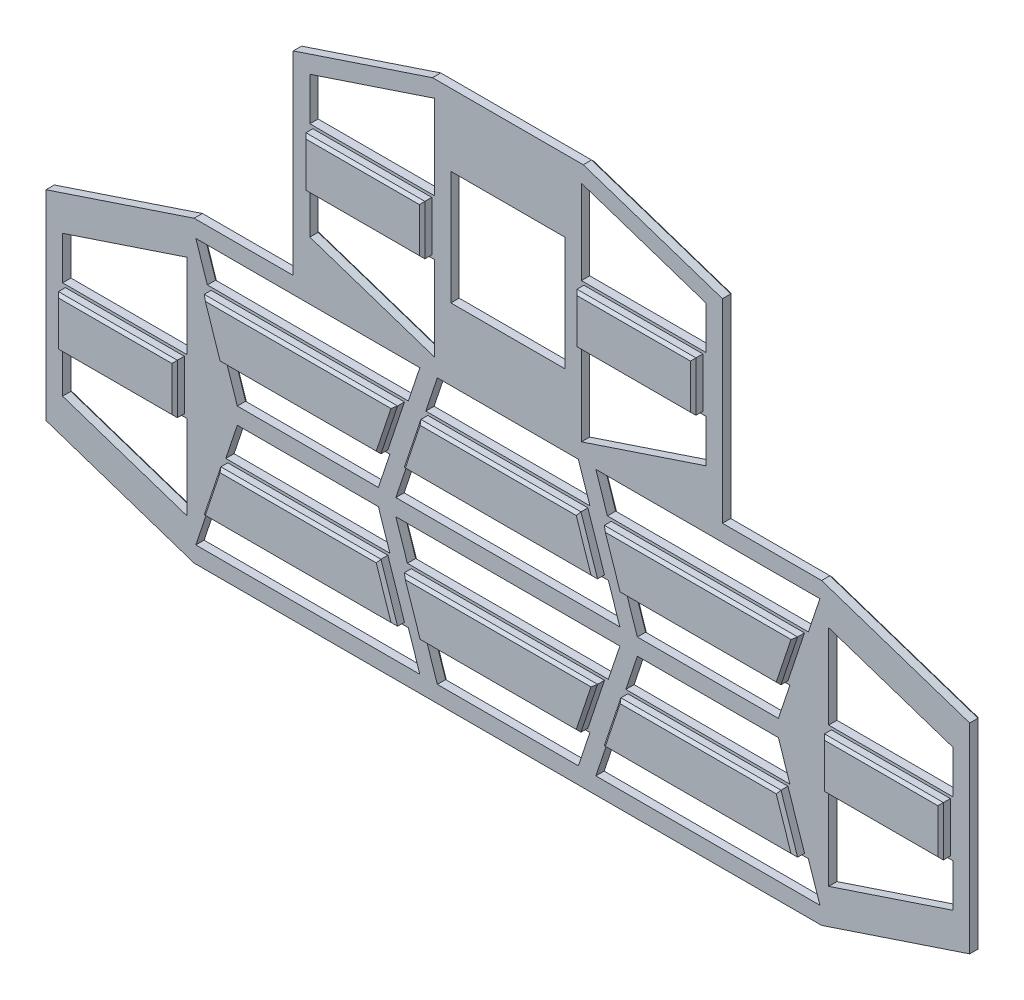
SolidWorks part; units mm, degrees
ref_plane "Front Plane" through (0, 0, 0) normal (0, 0, 1) x (1, 0, 0)
ref_plane "Top Plane" through (0, 0, 0) normal (0, 1, 0) x (1, 0, 0)
ref_plane "Right Plane" through (0, 0, 0) normal (1, 0, 0) x (0, 0, -1)
sketch "Sketch1" plane through (0, 0, 0) normal (0, 0, 1) x (1, 0, 0)
  line L0 (0, 37.8111) -> (0, -97.9817) construction
  line L1 (-53.0722, 0) -> (46.9222, 0) construction
  line L2 (-13.3, 20.25) -> (-13.3, -20.25)
  line L3 (-10.3, -10.3) -> (10.3, -10.3)
  line L4 (-10.3, -10.3) -> (-10.3, 10.3)
  line L5 (-10.3, 10.3) -> (10.3, 10.3)
  line L6 (10.3, -10.3) -> (10.3, 10.3)
  line L7 (-10.3, -10.3) -> (10.3, 10.3) construction
  line L8 (-10.3, 10.3) -> (10.3, -10.3) construction
  line L9 (-13.3, 20.25) -> (-35.8, 12.75)
  line L10 (-35.8, 12.75) -> (-35.8, -12.75)
  line L11 (-13.3, -20.25) -> (-35.8, -12.75)
  line L12 (13.3, -20.25) -> (35.8, -12.75)
  line L13 (35.8, 12.75) -> (35.8, -12.75)
  line L14 (13.3, 20.25) -> (35.8, 12.75)
  line L15 (13.3, 20.25) -> (13.3, -20.25)
  line L32 (48.9123, -48.75) -> (56.4123, -71.25)
  line L68 (-13.6368, 23.3) -> (13.6368, 23.3)
  line L69 (-38.8, 14.9123) -> (-13.6368, 23.3)
  line L70 (-90.3613, -47.25) -> (102.7928, -47.25) construction
  line L87 (-12.75, -23.25) -> (12.75, -23.25)
  line L88 (12.75, -23.25) -> (20.25, -45.75)
  line L89 (20.25, -45.75) -> (-20.25, -45.75)
  line L90 (-20.25, -45.75) -> (-12.75, -23.25)
  line L91 (15.9123, -23.25) -> (23.4123, -45.75)
  line L92 (23.4123, -45.75) -> (48.9123, -45.75)
  line L93 (48.9123, -45.75) -> (56.4123, -23.25)
  line L94 (56.4123, -23.25) -> (15.9123, -23.25)
  line L95 (-48.9123, -45.75) -> (-56.4123, -23.25)
  line L96 (-23.4123, -45.75) -> (-48.9123, -45.75)
  line L97 (-15.9123, -23.25) -> (-23.4123, -45.75)
  line L98 (-56.4123, -23.25) -> (-15.9123, -23.25)
  line L99 (23.4123, -48.75) -> (48.9123, -48.75)
  line L100 (15.9123, -71.25) -> (23.4123, -48.75)
  line L101 (56.4123, -71.25) -> (15.9123, -71.25)
  line L102 (-23.4123, -48.75) -> (-48.9123, -48.75)
  line L103 (-15.9123, -71.25) -> (-23.4123, -48.75)
  line L104 (-56.4123, -71.25) -> (-15.9123, -71.25)
  line L105 (-48.9123, -48.75) -> (-56.4123, -71.25)
  line L106 (20.25, -48.75) -> (-20.25, -48.75)
  line L107 (12.75, -71.25) -> (20.25, -48.75)
  line L108 (-12.75, -71.25) -> (12.75, -71.25)
  line L109 (-20.25, -48.75) -> (-12.75, -71.25)
  line L110 (58, -67.5) -> (58, -27)
  line L111 (58, -27) -> (80.5, -34.5)
  line L112 (80.5, -34.5) -> (80.5, -60)
  line L113 (58, -67.5) -> (80.5, -60)
  line L114 (-58, -27) -> (-80.5, -34.5)
  line L115 (-58, -67.5) -> (-58, -27)
  line L116 (-58, -67.5) -> (-80.5, -60)
  line L117 (-80.5, -34.5) -> (-80.5, -60)
  line L118 (56.7237, -74.25) -> (-56.7237, -74.25)
  line L119 (-83.5, -65.3246) -> (-83.5, -29.1754)
  line L120 (-38.8, 14.9123) -> (-38.8, -20.25)
  line L121 (-38.8, -20.25) -> (-56.7237, -20.25)
  line L122 (-83.5, -65.3246) -> (-56.7237, -74.25)
  line L123 (-83.5, -29.1754) -> (-56.7237, -20.25)
  line L124 (83.5, -65.3246) -> (56.7237, -74.25)
  line L125 (83.5, -65.3246) -> (83.5, -29.1754)
  line L126 (83.5, -29.1754) -> (56.7237, -20.25)
  line L127 (38.8, -20.25) -> (56.7237, -20.25)
  line L128 (38.8, 14.9123) -> (38.8, -20.25)
  line L129 (38.8, 14.9123) -> (13.6368, 23.3)
  point P5 (0, 0)
  point P18 (-35.8, 0)
  point P19 (-13.3, 0)
  point P23 (13.3, 0)
  point P24 (35.8, 0)
  point P54 (80.5, -47.25)
  point P55 (58, -47.25)
  point P64 (0, -75.25)
  point P68 (0, -74.25)
  point P71 (0, 23.25)
  point P77 (0, 23.3)
  dimension "D1" = 20.6
  dimension "D2" = 20.6
  dimension "D3" = 3
  dimension "D4" = 22.5
  dimension "D5" = 12.75
  dimension "D6" = 20.25
  dimension "D7" = 12.75
  dimension "D8" = 25.5
  dimension "D9" = 40.5
  dimension "D10" = 22.5
  dimension "D11" = 13
  dimension "D12" = 20.25
  dimension "D13" = 3
  dimension "D14" = 40.5
  dimension "D15" = 25.5
  dimension "D16" = 22.5
  dimension "D17" = 3
  dimension "D18" = 3
  dimension "D19" = 1.5
  dimension "D20" = 12.75
  dimension "D21" = 20.25
  dimension "D22" = 22.5
  dimension "D23" = 58
  dimension "D24" = 3
  dimension "D25" = 3
  dimension "D26" = 3
  dimension "D28" = 6
  dimension "D36" = 3
extrude "Boss-Extrude1" add sketch "Sketch1" along normal blind 2
sketch "Sketch2" plane through (0, 0, 0) normal (0, 0, 1) x (1, 0, 0)
  line L1 (80.5, -60) -> (80.5, -34.5) construction
  line L4 (-80.5, -42.25) -> (-58, -42.25)
  line L5 (15.9123, -23.25) -> (23.4123, -45.75) construction
  line L6 (-80.5, -52.25) -> (-58, -52.25)
  line L7 (48.9123, -45.75) -> (56.4123, -23.25) construction
  line L8 (56.4123, -71.25) -> (48.9123, -48.75) construction
  line L9 (80.5, -52.25) -> (58, -52.25)
  line L10 (23.4123, -48.75) -> (15.9123, -71.25) construction
  line L11 (80.5, -42.25) -> (58, -42.25)
  line L12 (-58, -52.25) -> (-58, -42.25)
  line L13 (12.75, -71.25) -> (20.25, -48.75) construction
  line L14 (58, -42.25) -> (58, -52.25)
  line L15 (-20.25, -48.75) -> (-12.75, -71.25) construction
  line L17 (20.25, -45.75) -> (12.75, -23.25) construction
  line L19 (-12.75, -23.25) -> (-20.25, -45.75) construction
  line L20 (-15.9123, -71.25) -> (-23.4123, -48.75) construction
  line L22 (-48.9123, -48.75) -> (-56.4123, -71.25) construction
  line L24 (-23.4123, -45.75) -> (-15.9123, -23.25) construction
  line L26 (-56.4123, -23.25) -> (-48.9123, -45.75) construction
  line L30 (-80.5, -34.5) -> (-80.5, -60) construction
  line L33 (35.8, -12.75) -> (35.8, 12.75) construction
  line L35 (13.3, 20.25) -> (13.3, -20.25) construction
  line L36 (-13.3, -20.25) -> (-13.3, 20.25) construction
  line L38 (-35.8, 12.75) -> (-35.8, -12.75) construction
  line L41 (80.5, -52.25) -> (80.5, -42.25)
  line L45 (17.9956, -29.5) -> (21.3289, -39.5)
  line L47 (50.9956, -39.5) -> (54.3289, -29.5)
  line L48 (54.3289, -65) -> (50.9956, -55)
  line L50 (21.3289, -55) -> (17.9956, -65)
  line L53 (14.8333, -65) -> (18.1667, -55)
  line L55 (-18.1667, -55) -> (-14.8333, -65)
  line L57 (18.1667, -39.5) -> (14.8333, -29.5)
  line L59 (-14.8333, -29.5) -> (-18.1667, -39.5)
  line L60 (-17.9956, -65) -> (-21.3289, -55)
  line L62 (-50.9956, -55) -> (-54.3289, -65)
  line L64 (-21.3289, -39.5) -> (-17.9956, -29.5)
  line L66 (-54.3289, -29.5) -> (-50.9956, -39.5)
  line L70 (-80.5, -42.25) -> (-80.5, -52.25)
  line L73 (35.8, -5) -> (35.8, 5)
  line L75 (13.3, 5) -> (13.3, -5)
  line L76 (-13.3, -5) -> (-13.3, 5)
  line L78 (-35.8, 5) -> (-35.8, -5)
  line L80 (-53.1836, 0) -> (59.8744, 0) construction
  line L81 (-35.8, 5) -> (-13.3, 5)
  line L82 (-35.8, -5) -> (-13.3, -5)
  line L83 (0, 26.2723) -> (0, -75.7168) construction
  line L84 (-97.7099, -34.5) -> (105.0284, -34.5) construction
  line L85 (-100.8051, -60) -> (103.6215, -60) construction
  line L86 (-87.2986, -47.25) -> (95.7427, -47.25) construction
  line L87 (-54.3289, -29.5) -> (-17.9956, -29.5)
  line L88 (-14.8333, -29.5) -> (14.8333, -29.5)
  line L89 (17.9956, -29.5) -> (54.3289, -29.5)
  line L90 (-50.9956, -39.5) -> (-21.3289, -39.5)
  line L91 (-18.1667, -39.5) -> (18.1667, -39.5)
  line L92 (21.3289, -39.5) -> (50.9956, -39.5)
  line L93 (21.3289, -55) -> (50.9956, -55)
  line L94 (17.9956, -65) -> (54.3289, -65)
  line L95 (-14.8333, -65) -> (14.8333, -65)
  line L96 (-18.1667, -55) -> (18.1667, -55)
  line L97 (-50.9956, -55) -> (-21.3289, -55)
  line L98 (-54.3289, -65) -> (-17.9956, -65)
  line L99 (35.8, -5) -> (13.3, -5)
  line L100 (35.8, 5) -> (13.3, 5)
  dimension "D1" = 5
  dimension "D2" = 34.5
  dimension "D3" = 60
  dimension "D4" = 5
  dimension "D5" = 5
  dimension "D6" = 5
extrude "Boss-Extrude2" add sketch "Sketch2" along normal blind 2
sketch "Sketch3" plane through (0, 0, 2) normal (0, 0, 1) x (1, 0, 0)
  line L0 (0, 34.8891) -> (0, -79.5414) construction
  line L1 (-49.4092, 0) -> (56.9579, 0) construction
  line L2 (-89.3827, -47.25) -> (98.1322, -47.25) construction
  line L3 (-93.6717, -34.5) -> (104.6515, -34.5) construction
  line L4 (-96.9313, -60) -> (102.4212, -60) construction
  line L5 (-13.75, -4.5) -> (-35.25, -4.5)
  line L10 (-35.25, 4.5) -> (-35.25, -4.5)
  line L11 (-13.75, 4.5) -> (-35.25, 4.5)
  line L12 (-13.75, 4.5) -> (-13.75, -4.5)
  line L13 (13.75, 4.5) -> (13.75, -4.5)
  line L14 (13.75, 4.5) -> (35.25, 4.5)
  line L15 (35.25, 4.5) -> (35.25, -4.5)
  line L16 (13.75, -4.5) -> (35.25, -4.5)
  line L33 (-17.473, -39) -> (17.473, -39)
  line L34 (17.473, -39) -> (14.473, -30)
  line L35 (14.473, -30) -> (-14.473, -30)
  line L36 (-14.473, -30) -> (-17.473, -39)
  line L37 (21.6893, -39) -> (50.6352, -39)
  line L38 (50.6352, -39) -> (53.6352, -30)
  line L39 (53.6352, -30) -> (18.6893, -30)
  line L40 (18.6893, -30) -> (21.6893, -39)
  line L41 (-53.6352, -30) -> (-18.6893, -30)
  line L42 (-18.6893, -30) -> (-21.6893, -39)
  line L43 (-21.6893, -39) -> (-50.6352, -39)
  line L44 (-50.6352, -39) -> (-53.6352, -30)
  line L45 (18.6893, -64.5) -> (21.6893, -55.5)
  line L46 (53.6352, -64.5) -> (18.6893, -64.5)
  line L47 (50.6352, -55.5) -> (53.6352, -64.5)
  line L48 (21.6893, -55.5) -> (50.6352, -55.5)
  line L49 (-14.473, -64.5) -> (-17.473, -55.5)
  line L50 (14.473, -64.5) -> (-14.473, -64.5)
  line L51 (17.473, -55.5) -> (14.473, -64.5)
  line L52 (-17.473, -55.5) -> (17.473, -55.5)
  line L53 (-50.6352, -55.5) -> (-53.6352, -64.5)
  line L54 (-21.6893, -55.5) -> (-50.6352, -55.5)
  line L55 (-18.6893, -64.5) -> (-21.6893, -55.5)
  line L56 (-53.6352, -64.5) -> (-18.6893, -64.5)
  line L57 (-58.5, -42.75) -> (-80, -42.75)
  line L62 (-80, -42.75) -> (-80, -51.75)
  line L63 (-58.5, -51.75) -> (-80, -51.75)
  line L64 (-58.5, -42.75) -> (-58.5, -51.75)
  line L65 (58.5, -42.75) -> (58.5, -51.75)
  line L66 (58.5, -51.75) -> (80, -51.75)
  line L67 (80, -42.75) -> (80, -51.75)
  line L68 (58.5, -42.75) -> (80, -42.75)
  dimension "D1" = 34.5
  dimension "D2" = 60
  dimension "D3" = 47.25
  dimension "D4" = 13.75
extrude "Boss-Extrude3" add sketch "Sketch3" along normal blind 1.75
chamfer "Chamfer1" distance 0.5 angle 45 138 edges at (80, -47.25, 3.75) (69.25, -51.75, 3.75) (58.5, -47.25, 3.75) (69.25, -42.75, 3.75) (-69.25, -51.75, 3.75) (-80, -47.25, 3.75) (-69.25, -42.75, 3.75) (-58.5, -47.25, 3.75) (-20.1893, -60, 3.75) (-36.1623, -64.5, 3.75) (-52.1352, -60, 3.75) (-36.1623, -55.5, 3.75) (-15.973, -60, 3.75) (0, -55.5, 3.75) (15.973, -60, 3.75) (0, -64.5, 3.75) (20.1893, -60, 3.75) (36.1623, -55.5, 3.75) (52.1352, -60, 3.75) (36.1623, -64.5, 3.75) (36.1623, -30, 3.75) (52.1352, -34.5, 3.75) (36.1623, -39, 3.75) (20.1893, -34.5, 3.75) (0, -30, 3.75) (15.973, -34.5, 3.75) (0, -39, 3.75) (-15.973, -34.5, 3.75) (-36.1623, -30, 3.75) (-20.1893, -34.5, 3.75) (-36.1623, -39, 3.75) (-52.1352, -34.5, 3.75) (-24.5, -4.5, 3.75) (-35.25, 0, 3.75) (-24.5, 4.5, 3.75) (-13.75, 0, 3.75) (35.25, 0, 3.75) (24.5, -4.5, 3.75) (13.75, 0, 3.75) (24.5, 4.5, 3.75) (69.25, -30.75, 0) (80.5, -38.375, 0) (69.25, -42.25, 0) (58, -34.625, 0) (-80.5, -56.125, 0) (-69.25, -52.25, 0) (-58, -59.875, 0) (-69.25, -63.75, 0) (-13.7917, -68.125, 0) (0, -65, 0) (13.7917, -68.125, 0) (0, -71.25, 0) (-55.3706, -68.125, 0) (-36.1623, -65, 0) (-16.9539, -68.125, 0) (-36.1623, -71.25, 0) (36.1623, -48.75, 0) (49.9539, -51.875, 0) (36.1623, -55, 0) (22.3706, -51.875, 0) (-36.1623, -45.75, 0) (-49.9539, -42.625, 0) (-36.1623, -39.5, 0) (-22.3706, -42.625, 0) (36.1623, -23.25, 0) (55.3706, -26.375, 0) (36.1623, -29.5, 0) (16.9539, -26.375, 0) (13.7917, -26.375, 0) (0, -29.5, 0) (-13.7917, -26.375, 0) (0, -23.25, 0) (35.8, 8.875, 0) (24.55, 5, 0) (13.3, 12.625, 0) (24.55, 16.5, 0) (-24.55, 16.5, 0) (-13.3, 12.625, 0) (-24.55, 5, 0) (-35.8, 8.875, 0) (-10.3, 0, 0) (0, 10.3, 0) (10.3, 0, 0) (0, -10.3, 0) (-38.8, -2.6689, 0) (-47.7618, -20.25, 0) (-70.1118, -24.7127, 0) (-83.5, -47.25, 0) (-70.1118, -69.7873, 0) (0, -74.25, 0) (70.1118, -69.7873, 0) (83.5, -47.25, 0) (70.1118, -24.7127, 0) (47.7618, -20.25, 0) (38.8, -2.6689, 0) (26.2184, 19.1061, 0) (0, 23.3, 0) (-26.2184, 19.1061, 0) (-13.3, -12.625, 0) (-24.55, -16.5, 0) (-35.8, -8.875, 0) (-24.55, -5, 0) (-55.3706, -26.375, 0) (-36.1623, -23.25, 0) (-16.9539, -26.375, 0) (-36.1623, -29.5, 0) (19.2083, -42.625, 0) (0, -45.75, 0) (-19.2083, -42.625, 0) (0, -39.5, 0) (49.9539, -42.625, 0) (36.1623, -45.75, 0) (22.3706, -42.625, 0) (36.1623, -39.5, 0) (55.3706, -68.125, 0) (36.1623, -71.25, 0) (16.9539, -68.125, 0) (36.1623, -65, 0) (-19.2083, -51.875, 0) (0, -48.75, 0) (19.2083, -51.875, 0) (0, -55, 0) (-49.9539, -51.875, 0) (-36.1623, -48.75, 0) (-22.3706, -51.875, 0) (-36.1623, -55, 0) (35.8, -8.875, 0) (24.55, -16.5, 0) (13.3, -12.625, 0) (24.55, -5, 0) (-80.5, -38.375, 0) (-69.25, -30.75, 0) (-58, -34.625, 0) (-69.25, -42.25, 0) (80.5, -56.125, 0) (69.25, -63.75, 0) (58, -59.875, 0) (69.25, -52.25, 0)
